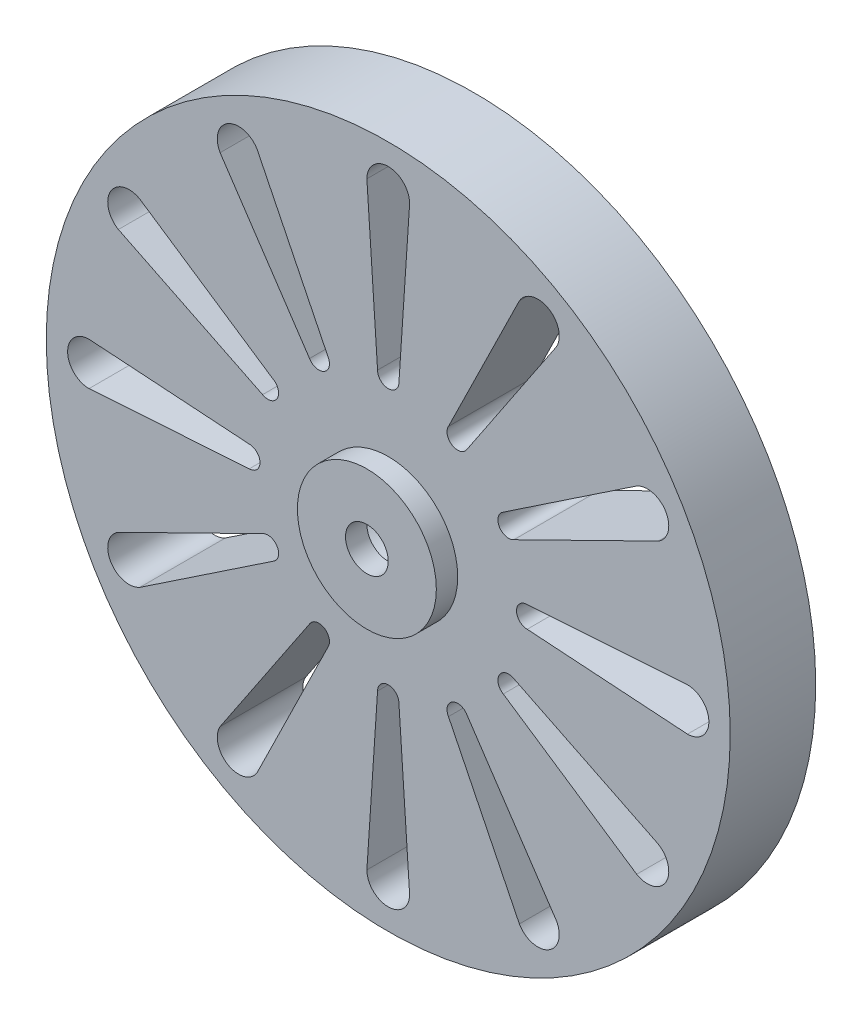
SolidWorks part; units mm, degrees
ref_plane "Plan de face" through (0, 0, 0) normal (0, 0, 1) x (1, 0, 0)
ref_plane "Plan de dessus" through (0, 0, 0) normal (0, 1, 0) x (1, 0, 0)
ref_plane "Plan de droite" through (0, 0, 0) normal (1, 0, 0) x (0, 0, -1)
sketch "Esquisse1" plane through (0, 0, 0) normal (0, 0, 1) x (1, 0, 0)
  circle A0 centre (0, 0) radius 16
  dimension "D1" = 32
extrude "Boss.-Extru.1" add sketch "Esquisse1" along normal blind 4
sketch "Esquisse2" plane through (0, 0, 4) normal (0, 0, 1) x (1, 0, 0)
  circle A0 centre (0, 0) radius 3.25
  dimension "D1" = 6.5
extrude "Boss.-Extru.2" add sketch "Esquisse2" along normal blind 1
sketch "Esquisse3" plane through (0, 0, 5) normal (0, 0, 1) x (1, 0, 0)
  circle A0 centre (0, 0) radius 1
  dimension "D1" = 2
extrude "Enlèv. mat.-Extru.1" cut sketch "Esquisse3" against normal up to next
sketch "Esquisse4" plane through (0, 0, 0) normal (0, 0, -1) x (-1, 0, 0)
  line L0 (-0.925, 0) -> (0.925, 0) construction
  line L1 (-0.925, 1.85) -> (0.925, 1.85)
  line L2 (-0.925, -1.85) -> (0.925, -1.85)
  arc A0 (-0.925, 1.85) -> (-0.925, -1.85) centre (-0.925, 0) ccw
  arc A1 (0.925, -1.85) -> (0.925, 1.85) centre (0.925, 0) ccw
  point P2 (0, 0)
  dimension "D1" = 3.7
  dimension "D2" = 1.85
extrude "Enlèv. mat.-Extru.2" cut sketch "Esquisse4" against normal blind 4 contours L1 A1 L2 A0
sketch "Esquisse5" plane through (0, 0, 0) normal (0, 0, -1) x (-1, 0, 0)
  line L2 (6.5, 0.5) -> (14, 1)
  line L3 (6.5, -0.5) -> (14, -1)
  arc A4 (6.5, 0.5) -> (6.5, -0.5) centre (6.5, 0) ccw
  arc A5 (14, 1) -> (14, -1) centre (14, 0) cw
  dimension "D1" = 6.5
  dimension "D2" = 0.5
  dimension "D4" = 1
  dimension "D3" = 14
  dimension "D5" = 6.5
  dimension "D6" = 0.5
  dimension "D7" = 1
  dimension "D8" = 14
extrude "Enlèv. mat.-Extru.4" cut sketch "Esquisse5" against normal up to next contours L2 A5 L3 A4
pattern_circular "Répétition circulaire1" count 12 over 360 about axis through (0, 0, 0) along (0, 0, 1) of "Enlèv. mat.-Extru.4"
